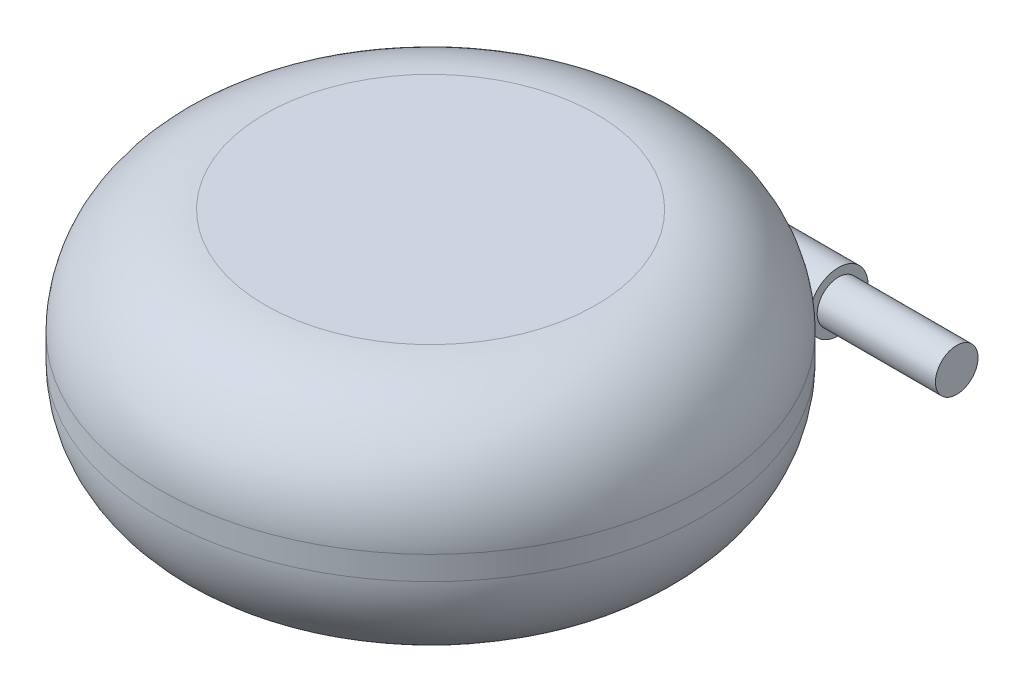
SolidWorks part; units mm, degrees
ref_plane "Front Plane" through (0, 0, 0) normal (0, 0, 1) x (1, 0, 0)
ref_plane "Top Plane" through (0, 0, 0) normal (0, 1, 0) x (1, 0, 0)
ref_plane "Right Plane" through (0, 0, 0) normal (1, 0, 0) x (0, 0, -1)
sketch "Sketch1" plane through (0, 0, 0) normal (0, 1, 0) x (1, 0, 0)
  circle A0 centre (0, 0) radius 29.21
  dimension "D1" = 58.42
extrude "Boss-Extrude1" add sketch "Sketch1" along normal blind 25.4
fillet "Fillet1" radius 11.43 2 edges at (0, 0, 29.21) (0, 25.4, 29.21)
sketch "Sketch2" plane through (0, 0, 0) normal (1, 0, 0) x (0, 0, -1)
  line L0 (-29.21, 12.7) -> (29.21, 12.7) construction
  line L1 (-29.21, 13.97) -> (-29.21, 11.43) construction
  line L2 (29.21, 11.43) -> (29.21, 13.97) construction
  circle A0 centre (26.035, 12.7) radius 3.175
  dimension "D1" = 6.35
extrude "Boss-Extrude2" add sketch "Sketch2" along normal blind 17.78
sketch "Sketch3" plane through (17.78, 0, 0) normal (1, 0, 0) x (0, 0, -1)
  circle A0 centre (26.035, 12.7) radius 2.286
  dimension "D1" = 4.572
extrude "Boss-Extrude3" add sketch "Sketch3" along normal blind 12.7
